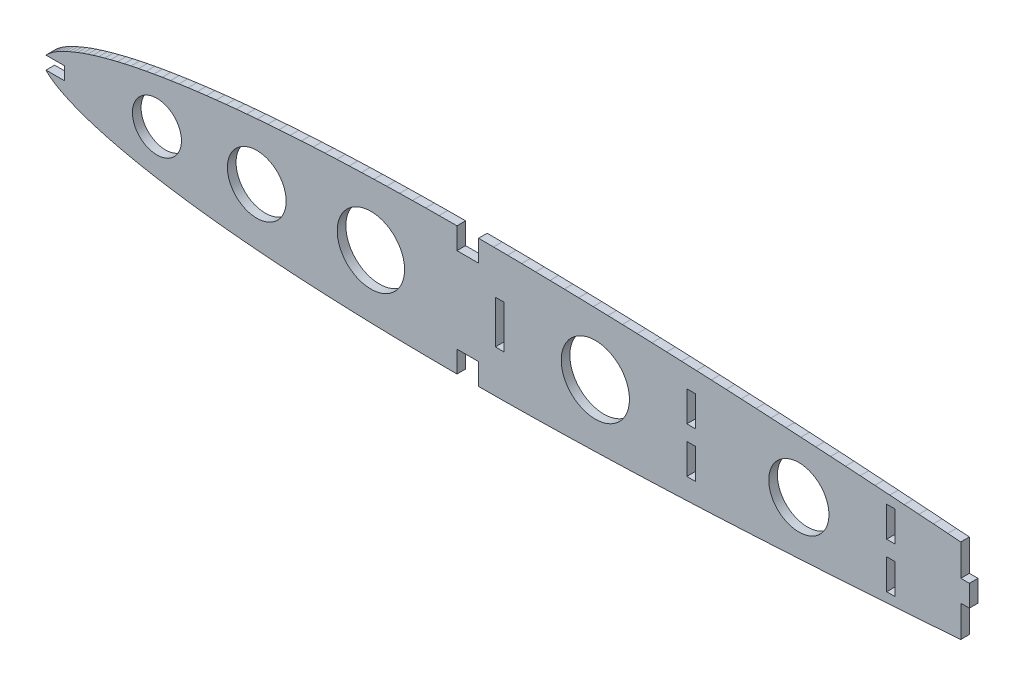
SolidWorks part; units mm, degrees
ref_plane "前视基准面" through (0, 0, 0) normal (0, 0, 1) x (1, 0, 0)
ref_plane "上视基准面" through (0, 0, 0) normal (0, 1, 0) x (1, 0, 0)
ref_plane "右视基准面" through (0, 0, 0) normal (1, 0, 0) x (0, 0, -1)
sketch "Model" plane through (0, 0, 0) normal (0, 0, 1) x (1, 0, 0)
  line L0 (168.3781, 72.0437) -> (166.3761, 72.0437)
  line L2 (168.3781, 62.0437) -> (166.3761, 62.0437)
  line L3 (166.3761, 72.0437) -> (166.3761, 62.0437)
  line L4 (62.1174, 68.5437) -> (66.3761, 68.5437)
  line L5 (66.3761, 68.5437) -> (66.3761, 65.5437)
  line L6 (66.3761, 65.5437) -> (62.1174, 65.5437)
  line L8 (162.4821, 57.1477) -> (157.4821, 57.1467)
  line L10 (274.376, 76.8493) -> (271.3641, 77.0747)
  line L11 (271.3641, 77.0747) -> (268.0361, 77.3177)
  line L12 (268.0361, 77.3177) -> (264.6531, 77.5607)
  line L13 (264.6531, 77.5607) -> (261.2711, 77.7987)
  line L14 (261.2711, 77.7987) -> (257.8871, 78.0327)
  line L15 (257.8871, 78.0327) -> (254.4651, 78.2657)
  line L16 (254.4651, 78.2657) -> (251.0431, 78.4937)
  line L17 (251.0431, 78.4937) -> (247.6201, 78.7147)
  line L18 (247.6201, 78.7147) -> (244.1691, 78.9297)
  line L19 (244.1691, 78.9297) -> (240.7181, 79.1387)
  line L20 (240.7181, 79.1387) -> (237.2661, 79.3437)
  line L21 (237.2661, 79.3437) -> (233.8031, 79.5457)
  line L22 (233.8031, 79.5457) -> (230.3401, 79.7447)
  line L23 (230.3401, 79.7447) -> (226.8761, 79.9357)
  line L24 (226.8761, 79.9357) -> (223.4131, 80.1197)
  line L25 (223.4131, 80.1197) -> (219.9501, 80.2947)
  line L26 (219.9501, 80.2947) -> (216.4861, 80.4627)
  line L27 (216.4861, 80.4627) -> (213.0351, 80.6217)
  line L28 (213.0351, 80.6217) -> (209.5841, 80.7727)
  line L29 (209.5841, 80.7727) -> (206.1321, 80.9157)
  line L30 (206.1321, 80.9157) -> (202.7101, 81.0507)
  line L31 (202.7101, 81.0507) -> (199.2881, 81.1777)
  line L32 (199.2881, 81.1777) -> (195.8651, 81.2967)
  line L33 (195.8651, 81.2967) -> (192.4821, 81.4047)
  line L34 (192.4821, 81.4047) -> (189.1001, 81.5037)
  line L35 (189.1001, 81.5037) -> (185.7161, 81.5947)
  line L36 (185.7161, 81.5947) -> (182.3881, 81.6747)
  line L37 (182.3881, 81.6747) -> (179.0611, 81.7457)
  line L38 (179.0611, 81.7457) -> (175.7331, 81.8067)
  line L39 (175.7331, 81.8067) -> (172.4731, 81.8557)
  line L40 (172.4731, 81.8557) -> (169.2131, 81.8947)
  line L41 (169.2131, 81.8947) -> (165.9521, 81.9217)
  line L42 (165.9521, 81.9217) -> (162.4831, 81.9397)
  line L43 (210.8136, 68.805) -> (210.8136, 75.8504)
  line L44 (210.8136, 65.2823) -> (210.8136, 58.237)
  line L45 (212.8136, 75.8504) -> (212.8136, 68.805)
  line L46 (212.8136, 65.2823) -> (212.8136, 58.237)
  line L48 (168.3781, 72.0437) -> (168.3781, 62.0437)
  line L50 (257.1747, 68.805) -> (257.1747, 75.8504)
  line L51 (257.1747, 65.2823) -> (257.1747, 58.237)
  line L52 (162.4831, 81.9397) -> (162.4811, 76.9397)
  line L53 (162.4811, 76.9397) -> (157.4811, 76.9407)
  line L54 (157.4811, 76.9407) -> (157.4831, 81.9387)
  line L55 (162.4831, 52.1477) -> (162.4821, 57.1477)
  line L57 (157.4821, 57.1467) -> (157.4831, 52.1467)
  line L58 (210.8136, 75.8504) -> (212.8136, 75.8504)
  line L59 (210.8136, 68.805) -> (212.8136, 68.805)
  line L60 (210.8136, 65.2823) -> (212.8136, 65.2823)
  line L61 (210.8136, 58.237) -> (212.8136, 58.237)
  line L62 (257.1747, 75.8504) -> (259.1747, 75.8504)
  line L63 (257.1747, 68.805) -> (259.1747, 68.805)
  line L64 (257.1747, 65.2823) -> (259.1747, 65.2823)
  line L65 (257.1747, 58.237) -> (259.1747, 58.237)
  line L66 (259.1747, 75.8504) -> (259.1747, 68.805)
  line L67 (259.1747, 65.2823) -> (259.1747, 58.237)
  line L68 (276.376, 67.0437) -> (276.376, 69.5437)
  line L69 (276.376, 67.0437) -> (276.376, 64.5437)
  line L70 (276.376, 69.5437) -> (274.376, 69.5437)
  line L71 (276.376, 64.5437) -> (274.376, 64.5437)
  line L72 (274.376, 69.5437) -> (274.376, 76.8493)
  line L73 (274.376, 64.5437) -> (274.376, 57.2381)
  line L74 (162.4831, 52.1477) -> (165.9521, 52.1657)
  line L75 (165.9521, 52.1657) -> (169.2131, 52.1927)
  line L76 (169.2131, 52.1927) -> (172.4731, 52.2317)
  line L77 (172.4731, 52.2317) -> (175.7331, 52.2807)
  line L78 (175.7331, 52.2807) -> (179.0611, 52.3417)
  line L79 (179.0611, 52.3417) -> (182.3881, 52.4127)
  line L80 (182.3881, 52.4127) -> (185.7161, 52.4927)
  line L81 (185.7161, 52.4927) -> (189.1001, 52.5837)
  line L82 (189.1001, 52.5837) -> (192.4821, 52.6827)
  line L83 (192.4821, 52.6827) -> (195.8651, 52.7907)
  line L84 (195.8651, 52.7907) -> (199.2881, 52.9097)
  line L85 (199.2881, 52.9097) -> (202.7101, 53.0367)
  line L86 (202.7101, 53.0367) -> (206.1321, 53.1717)
  line L87 (206.1321, 53.1717) -> (209.5841, 53.3147)
  line L88 (209.5841, 53.3147) -> (213.0351, 53.4657)
  line L89 (213.0351, 53.4657) -> (216.4861, 53.6247)
  line L90 (216.4861, 53.6247) -> (219.9501, 53.7927)
  line L91 (219.9501, 53.7927) -> (223.4131, 53.9677)
  line L92 (223.4131, 53.9677) -> (226.8761, 54.1517)
  line L93 (226.8761, 54.1517) -> (230.3401, 54.3427)
  line L94 (230.3401, 54.3427) -> (233.8031, 54.5417)
  line L95 (233.8031, 54.5417) -> (237.2661, 54.7437)
  line L96 (237.2661, 54.7437) -> (240.7181, 54.9487)
  line L97 (240.7181, 54.9487) -> (244.1691, 55.1577)
  line L98 (244.1691, 55.1577) -> (247.6201, 55.3727)
  line L99 (247.6201, 55.3727) -> (251.0431, 55.5937)
  line L100 (251.0431, 55.5937) -> (254.4651, 55.8217)
  line L101 (254.4651, 55.8217) -> (257.8871, 56.0547)
  line L102 (257.8871, 56.0547) -> (261.2711, 56.2887)
  line L103 (261.2711, 56.2887) -> (264.6531, 56.5267)
  line L104 (264.6531, 56.5267) -> (268.0361, 56.7697)
  line L105 (268.0361, 56.7697) -> (271.3641, 57.0127)
  line L106 (271.3641, 57.0127) -> (274.376, 57.2381)
  line L107 (157.4831, 81.9387) -> (153.3211, 81.9217)
  line L108 (153.3211, 81.9217) -> (150.2331, 81.8937)
  line L109 (150.2331, 81.8937) -> (147.1451, 81.8527)
  line L110 (147.1451, 81.8527) -> (144.1621, 81.8007)
  line L111 (144.1621, 81.8007) -> (141.1801, 81.7357)
  line L112 (141.1801, 81.7357) -> (138.1981, 81.6577)
  line L113 (138.1981, 81.6577) -> (135.3311, 81.5697)
  line L114 (135.3311, 81.5697) -> (132.4651, 81.4677)
  line L115 (132.4651, 81.4677) -> (129.5981, 81.3527)
  line L116 (129.5981, 81.3527) -> (126.8591, 81.2297)
  line L117 (126.8591, 81.2297) -> (124.1211, 81.0917)
  line L118 (124.1211, 81.0917) -> (121.3831, 80.9387)
  line L119 (121.3831, 80.9387) -> (118.7821, 80.7787)
  line L120 (118.7821, 80.7787) -> (116.1831, 80.6037)
  line L121 (116.1831, 80.6037) -> (113.5851, 80.4127)
  line L122 (113.5851, 80.4127) -> (111.1331, 80.2167)
  line L123 (111.1331, 80.2167) -> (108.6821, 80.0057)
  line L124 (108.6821, 80.0057) -> (106.2331, 79.7777)
  line L125 (106.2331, 79.7777) -> (103.9381, 79.5477)
  line L126 (103.9381, 79.5477) -> (101.6461, 79.3027)
  line L127 (101.6461, 79.3027) -> (99.3551, 79.0387)
  line L128 (99.3551, 79.0387) -> (97.2281, 78.7767)
  line L129 (97.2281, 78.7767) -> (95.1051, 78.4977)
  line L130 (95.1051, 78.4977) -> (92.9831, 78.1987)
  line L131 (92.9831, 78.1987) -> (91.0331, 77.9047)
  line L132 (91.0331, 77.9047) -> (89.0851, 77.5937)
  line L133 (89.0851, 77.5937) -> (87.1411, 77.2617)
  line L134 (87.1411, 77.2617) -> (85.3731, 76.9407)
  line L135 (85.3731, 76.9407) -> (83.6091, 76.6007)
  line L136 (83.6091, 76.6007) -> (81.8481, 76.2387)
  line L137 (81.8481, 76.2387) -> (80.2701, 75.8927)
  line L138 (80.2701, 75.8927) -> (78.6971, 75.5257)
  line L139 (78.6971, 75.5257) -> (77.1281, 75.1367)
  line L140 (77.1281, 75.1367) -> (75.7451, 74.7717)
  line L141 (75.7451, 74.7717) -> (74.3681, 74.3857)
  line L142 (74.3681, 74.3857) -> (72.9971, 73.9747)
  line L143 (72.9971, 73.9747) -> (71.8141, 73.5947)
  line L144 (71.8141, 73.5947) -> (70.6401, 73.1897)
  line L145 (70.6401, 73.1897) -> (69.4761, 72.7567)
  line L146 (69.4761, 72.7567) -> (68.4991, 72.3657)
  line L147 (68.4991, 72.3657) -> (67.5321, 71.9507)
  line L148 (67.5321, 71.9507) -> (66.5761, 71.5127)
  line L149 (66.5761, 71.5127) -> (65.8061, 71.1357)
  line L150 (65.8061, 71.1357) -> (65.0481, 70.7347)
  line L151 (65.0481, 70.7347) -> (64.3091, 70.3007)
  line L152 (64.3091, 70.3007) -> (63.7441, 69.9317)
  line L153 (63.7441, 69.9317) -> (63.1991, 69.5337)
  line L154 (63.1991, 69.5337) -> (62.6801, 69.1057)
  line L155 (62.6801, 69.1057) -> (62.3221, 68.7707)
  line L156 (62.3221, 68.7707) -> (62.1174, 68.5437)
  line L157 (62.1174, 65.5437) -> (62.3221, 65.3167)
  line L158 (62.3221, 65.3167) -> (62.6801, 64.9817)
  line L159 (62.6801, 64.9817) -> (63.1991, 64.5537)
  line L160 (63.1991, 64.5537) -> (63.7441, 64.1557)
  line L161 (63.7441, 64.1557) -> (64.3091, 63.7867)
  line L162 (64.3091, 63.7867) -> (65.0481, 63.3527)
  line L163 (65.0481, 63.3527) -> (65.8061, 62.9517)
  line L164 (65.8061, 62.9517) -> (66.5761, 62.5747)
  line L165 (66.5761, 62.5747) -> (67.5321, 62.1367)
  line L166 (67.5321, 62.1367) -> (68.4991, 61.7217)
  line L167 (68.4991, 61.7217) -> (69.4761, 61.3307)
  line L168 (69.4761, 61.3307) -> (70.6401, 60.8977)
  line L169 (70.6401, 60.8977) -> (71.8141, 60.4927)
  line L170 (71.8141, 60.4927) -> (72.9971, 60.1127)
  line L171 (72.9971, 60.1127) -> (74.3681, 59.7017)
  line L172 (74.3681, 59.7017) -> (75.7451, 59.3157)
  line L173 (75.7451, 59.3157) -> (77.1281, 58.9507)
  line L174 (77.1281, 58.9507) -> (78.6971, 58.5617)
  line L175 (78.6971, 58.5617) -> (80.2701, 58.1947)
  line L176 (80.2701, 58.1947) -> (81.8481, 57.8487)
  line L177 (81.8481, 57.8487) -> (83.6091, 57.4867)
  line L178 (83.6091, 57.4867) -> (85.3731, 57.1467)
  line L179 (85.3731, 57.1467) -> (87.1411, 56.8257)
  line L180 (87.1411, 56.8257) -> (89.0851, 56.4937)
  line L181 (89.0851, 56.4937) -> (91.0331, 56.1827)
  line L182 (91.0331, 56.1827) -> (92.9831, 55.8887)
  line L183 (92.9831, 55.8887) -> (95.1051, 55.5897)
  line L184 (95.1051, 55.5897) -> (97.2281, 55.3107)
  line L185 (97.2281, 55.3107) -> (99.3551, 55.0487)
  line L186 (99.3551, 55.0487) -> (101.6461, 54.7847)
  line L187 (101.6461, 54.7847) -> (103.9381, 54.5397)
  line L188 (103.9381, 54.5397) -> (106.2331, 54.3097)
  line L189 (106.2331, 54.3097) -> (108.6821, 54.0817)
  line L190 (108.6821, 54.0817) -> (111.1331, 53.8707)
  line L191 (111.1331, 53.8707) -> (113.5851, 53.6747)
  line L192 (113.5851, 53.6747) -> (116.1831, 53.4837)
  line L193 (116.1831, 53.4837) -> (118.7821, 53.3087)
  line L194 (118.7821, 53.3087) -> (121.3831, 53.1487)
  line L195 (121.3831, 53.1487) -> (124.1211, 52.9957)
  line L196 (124.1211, 52.9957) -> (126.8591, 52.8577)
  line L197 (126.8591, 52.8577) -> (129.5981, 52.7347)
  line L198 (129.5981, 52.7347) -> (132.4651, 52.6197)
  line L199 (132.4651, 52.6197) -> (135.3311, 52.5177)
  line L200 (135.3311, 52.5177) -> (138.1981, 52.4297)
  line L201 (138.1981, 52.4297) -> (141.1801, 52.3517)
  line L202 (141.1801, 52.3517) -> (144.1621, 52.2867)
  line L203 (144.1621, 52.2867) -> (147.1451, 52.2347)
  line L204 (147.1451, 52.2347) -> (150.2331, 52.1937)
  line L205 (150.2331, 52.1937) -> (153.3211, 52.1657)
  line L206 (153.3211, 52.1657) -> (157.4831, 52.1467)
  circle A0 centre (87.8561, 67.0437) radius 5.6878
  circle A1 centre (111.0261, 67.0437) radius 6.817
  circle A2 centre (137.5061, 67.0437) radius 7.8158
  circle A3 centre (189.5833, 67.0437) radius 7.9176
  circle A4 centre (236.8061, 67.0437) radius 6.9835
  point P10 (0, 0)
  point P12 (0, 0)
  point P18 (0, 0)
  point P19 (0, 0)
  point P20 (157.6276, 52.085)
  point P65 (0, 0)
  point P67 (0, 0)
  point P74 (162.551, 57.1477)
  point P220 (0, 0)
  point P221 (0, 0)
  point P222 (157.5766, 81.9387)
  point P223 (0, 0)
  point P224 (0, 0)
  point P225 (157.4821, 57.2381)
  point P226 (0, 0)
  point P227 (0, 0)
  point P228 (157.4821, 57.1477)
  point P229 (0, 0)
extrude "凸台-拉伸2" add sketch "Model" along normal blind 2
